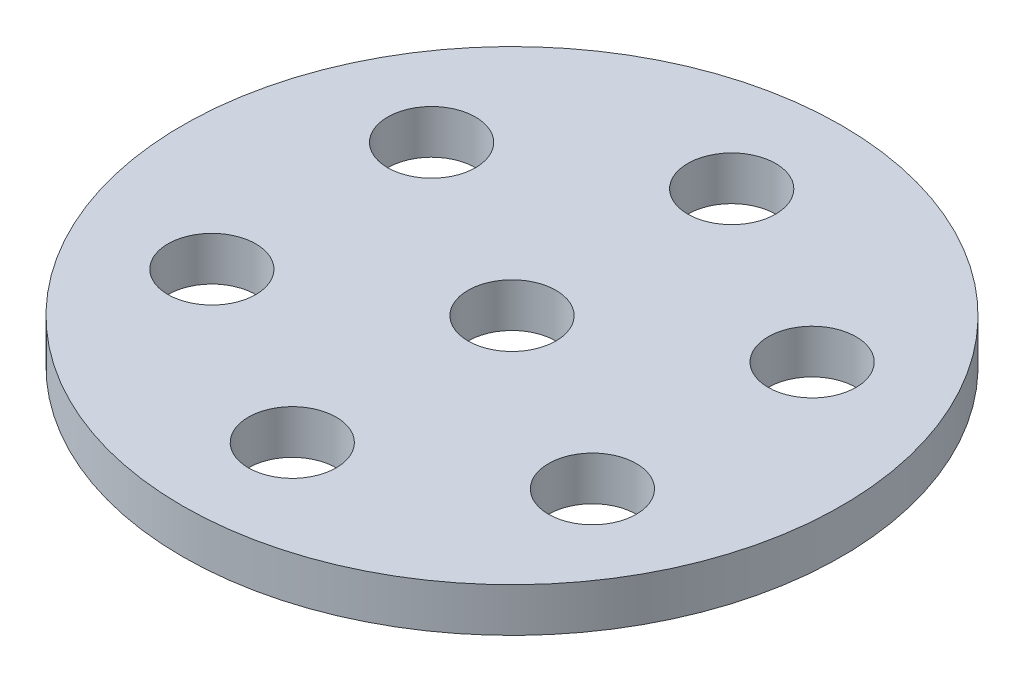
SolidWorks part; units mm, degrees
ref_plane "Front Plane" through (0, 0, 0) normal (0, 0, 1) x (1, 0, 0)
ref_plane "Top Plane" through (0, 0, 0) normal (0, 1, 0) x (1, 0, 0)
ref_plane "Right Plane" through (0, 0, 0) normal (1, 0, 0) x (0, 0, -1)
sketch "Sketch1" plane through (0, 0, 0) normal (0, 1, 0) x (1, 0, 0)
  line L0 (0, 75) -> (0, -75) construction
  line L1 (-75, 0) -> (75, 0) construction
  circle A0 centre (0, 0) radius 75
  circle A1 centre (0, 50) radius 10
  circle A2 centre (0, 0) radius 75
  circle A3 centre (43.3013, 25) radius 10
  circle A4 centre (0, 0) radius 75
  circle A5 centre (43.3013, -25) radius 10
  circle A6 centre (0, 0) radius 75
  circle A7 centre (0, -50) radius 10
  circle A8 centre (0, 0) radius 75
  circle A9 centre (-43.3013, -25) radius 10
  circle A10 centre (0, 0) radius 75
  circle A11 centre (-43.3013, 25) radius 10
  circle A12 centre (0, 0) radius 10
  point P26 (0, 0)
  dimension "D1" = 150
  dimension "D4" = 20
  dimension "D5" = 20
  dimension "D2" = 50
  dimension "D3" = 6
extrude "Boss-Extrude2" add sketch "Sketch1" along normal blind 10 contours A0 A12 A11 A9 A7 A5 A3 A1
